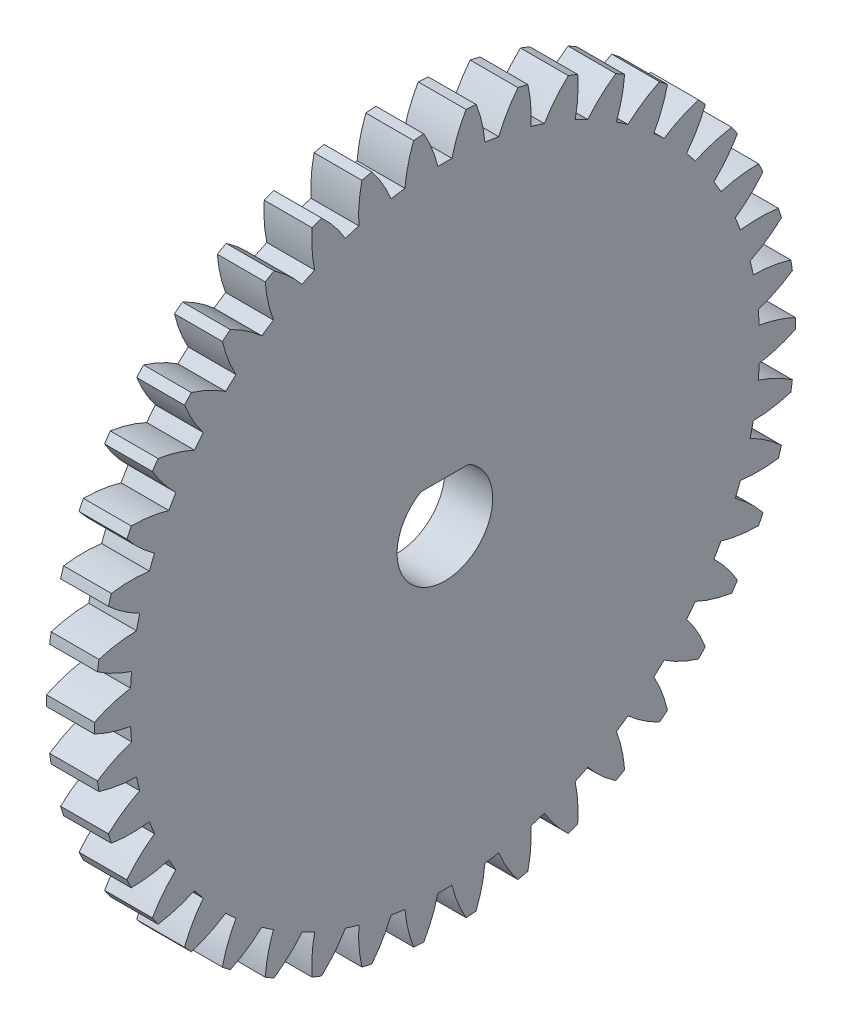
SolidWorks part; units mm, degrees
ref_plane "Plane1" through (0, 0, 0) normal (0, 0, 1) x (1, 0, 0)
ref_plane "Plane2" through (0, 0, 0) normal (0, 1, 0) x (1, 0, 0)
ref_plane "Plane3" through (0, 0, 0) normal (1, 0, 0) x (0, 0, -1)
other "Configuration Table"
sketch "HoldingSke" plane through (0, 0, 0) normal (0, 1, 0) x (1, 0, 0)
  line L0 (0, 0) -> (0.3716, -0.3346)
  line L1 (-15, 0) -> (100, 0) construction
  line L2 (0, 0) -> (-2.1039, 2.3779)
  line L3 (0, 0) -> (-11.863, 4.5341)
  line L4 (0, 0) -> (6.4178, 5.7786)
  line L5 (0, 0) -> (-46.8476, -17.4728)
  line L6 (0, 0) -> (-4.9738, -3.3558)
  line L7 (-2.1039, 2.3779) -> (8.6586, 51.2059)
  line L8 (-76.2, 54.61) -> (-73.9, 54.61)
  line L9 (-71.009, 38.7566) -> (-53.1078, 45.2721)
  line L10 (-76.2, 71.12) -> (104.1128, 71.12)
  line L11 (0, 0) -> (-6, 0)
  line L12 (-76.2, 101.6) -> (-76.133, 101.6)
  line L13 (24.9733, 27.94) -> (52.9518, 28.4284)
  line L14 (24.9733, 27.94) -> (24.9743, 27.94)
  line L15 (24.9733, 27.94) -> (100.4006, 29.5858)
  line L16 (-63.627, -2) -> (-12.827, -2)
  circle A0 centre (0, 0) radius 6
  circle A1 centre (0, 0) radius 37.5
  circle A2 centre (0, 0) radius 37.5
  circle A3 centre (0, 0) radius 6
  dimension "MHD" = 75
  dimension "Hub_dia" = 75
  dimension "Bore" = 12
  dimension "MBD" = 12
  dimension "Num_teeth" = 42
  dimension "Pitch" = 0.5
  dimension "Overall_len" = 50
  dimension "Show_teeth" = 42
  dimension "Thickness" = 6
  dimension "OAL" = 50.0001
  dimension "T_dim" = 2.3
  dimension "Ap" = 20
  dimension "H" = 19.05
  dimension "Pitch_radius" = 180.3128
  dimension "Width" = 6
  dimension "Backlash" = 0.067
  dimension "Addendum_fac" = 1
  dimension "Dedendum_fac" = 1.25
  dimension "Clearance_fac" = 0.25
  dimension "Dedendum_add" = 0.001
  dimension "Module" = 2
sketch "BasProSke" plane through (0, 0, 0) normal (0, 1, 0) x (1, 0, 0)
  line L0 (-10, 0) -> (60, 0) construction
  line L1 (0, 0) -> (0, 44)
  line L2 (0, 0) -> (6, 0)
  line L3 (6, 0) -> (6, 44)
  line L4 (6, 44) -> (0, 44)
  dimension "Thickness" = 6
  dimension "Diameter" = 88
revolve "Base-Revolve" add sketch "BasProSke" angle 360 about L0
sketch "TooCutSke" plane through (0, 0, 0) normal (1, 0, 0) x (0, 0, -1)
  line L1 (0, 0) -> (0, 107) construction
  line L2 (0, 0) -> (-1.6877, 41.9661) construction
  line L3 (0, 0) -> (-6.2736, 83.715) construction
  line L4 (-1.6877, 41.9661) -> (-3.1368, 41.8575) construction
  arc A0 (0.8776, 39.4892) -> (-0.8776, 39.4892) centre (0, 0) ccw
  arc A1 (2.6666, 43.9446) -> (-2.6666, 43.9446) centre (0, 0) ccw
  circle A2 centre (0, 0) radius 42 construction
  circle A3 centre (0, 0) radius 39.4671 construction
  arc A4 (-0.8776, 39.4892) -> (-2.6666, 43.9446) centre (-17.2022, 35.5209) ccw
  arc A5 (2.6666, 43.9446) -> (0.8776, 39.4892) centre (17.2022, 35.5209) ccw
  dimension "Root_dia" = 78.998
  dimension "Overcut_dia" = 88.0508
  dimension "Pitch_dia" = 84
  dimension "Base_dia" = 78.9342
  dimension "Flank_rad" = 16.8
  dimension "Half_ang" = 4.286
  dimension "Half_CT" = 1.4532
extrude "ToothCut" cut sketch "TooCutSke" along normal through all
fillet "Breaks" [suppressed] radius 0.04
fillet "RootFillets" [suppressed] radius 0.501
pattern_circular "TeethCuts" count 42 every 8.571 about axis through (-10, 0, 0) along (1, 0, 0) of "ToothCut", "RootFillets", "Breaks"
sketch "HubNeaOneSke" plane through (0, 0, 0) normal (-1, 0, 0) x (0, 0, 1)
  circle A0 centre (0, 0) radius 37.5
  dimension "Diameter" = 75
extrude "HubNearOne" [suppressed] add sketch "HubNeaOneSke" along normal blind 44.0001
sketch "HubNeaBotSke" plane through (0, 0, 0) normal (-1, 0, 0) x (0, 0, 1)
  circle A0 centre (0, 0) radius 37.5
  dimension "Diameter" = 75
extrude "HubNearBoth" [suppressed] add sketch "HubNeaBotSke" along normal blind 22
ref_plane "FarPln" through (6, 0, 0) normal (1, 0, 0) x (0, 0, -1)
sketch "HubFarSke" plane through (6, 0, 0) normal (1, 0, 0) x (0, 0, -1)
  circle A0 centre (0, 0) radius 37.5
  dimension "Diameter" = 75
extrude "HubFar" [suppressed] add sketch "HubFarSke" along normal blind 22
sketch "BorSke" plane through (0, 0, 0) normal (1, 0, 0) x (0, 0, -1)
  circle A0 centre (0, 0) radius 6
  dimension "Diameter" = 12
extrude "Bore" cut sketch "BorSke" along normal mid plane 100.0001
sketch "KeySke" plane through (0, 0, 0) normal (1, 0, 0) x (0, 0, -1)
  line L0 (-2.5, 0) -> (-2.5, 8.3)
  line L1 (-2.5, 8.3) -> (2.5, 8.3)
  line L2 (2.5, 8.3) -> (2.5, 0)
  line L3 (0, 0) -> (0, 34) construction
  line L4 (-2.5, 0) -> (2.5, 0)
  dimension "Offset" = 8.3
  dimension "Width" = 5
extrude "Keyway" [suppressed] cut sketch "KeySke" along normal mid plane 100.0001
pattern_circular "Keyway2" [suppressed] count 2 every 90 about axis through (-10, 0, 0) along (1, 0, 0)
sketch "Sketch1" plane through (6, 0, 0) normal (1, 0, 0) x (0, 0, -1)
  line L0 (-3, 5.1962) -> (3, 5.1962)
  circle A0 centre (0, 0) radius 6 construction
  circle A2 centre (0, 0) radius 6
  arc A3 (3, 5.1962) -> (-3, 5.1962) centre (0, 0) ccw
  dimension "D1" = 6
  dimension "D2" = 0
extrude "Boss-Extrude1" add sketch "Sketch1" against normal blind 6
equation "' \"Module@HoldingSke\" = 6.35"
equation "' \"Num_teeth@HoldingSke\" = 12"
equation "' \"Ap@HoldingSke\" =  20"
equation "' \"Ap@HoldingSke\" = 20"
equation "' \"Width@HoldingSke\" = 0.5 * 25.4"
equation "' \"Hub_dia@HoldingSke\"= 1 * 25.4"
equation "' \"Hub_dia@HoldingSke\" = 1 * 25.4"
equation "' \"Overall_len@HoldingSke\" = 1.0 * 25.4"
equation "' \"Bore@HoldingSke\" = 0.75 * 25.4"
equation "' \"T_dim@HoldingSke\" = 0.1 * 25.4"
equation "' \"Width@KeySke\" = 0.25 * 25.4"
equation "' \"Show_teeth@HoldingSke\" = 13"
equation "' \"Backlash@HoldingSke\" = 0.009 * 25.4"
equation "' \"Addendum_fac@HoldingSke\" = 1.0"
equation "' \"Dedendum_fac@HoldingSke\" = 1.25"
equation "' \"Dedendum_add@HoldingSke\" = 0.00005 * 25.4"
equation "' \"Clearance_fac@HoldingSke\" = 0.25"
equation "\"Pitch@HoldingSke\" = 1 / \"Module@HoldingSke\""
equation "\"Overcut_dia@TooCutSke\" = (\"Num_teeth@HoldingSke\" + 2 * \"Addendum_fac@HoldingSke\") / \"Pitch@HoldingSke\" + 0.002 * 25.4"
equation "\"Pitch_dia@TooCutSke\" = \"Num_teeth@HoldingSke\" / \"Pitch@HoldingSke\""
equation "\"Base_dia@TooCutSke\" = \"Num_teeth@HoldingSke\" / \"Pitch@HoldingSke\" * cos((\"Ap@HoldingSke\"  * 3.14159265 / 180))"
equation "\"Root_dia@TooCutSke\" = (\"Num_teeth@HoldingSke\" + 2) / \"Pitch@HoldingSke\" - 2 * (\"Addendum_fac@HoldingSke\" + \"Dedendum_fac@HoldingSke\") / \"Pitch@HoldingSke\" - \"Dedendum_add@HoldingSke\" * 2"
equation "\"Half_ang@TooCutSke\" = 180 / \"Num_teeth@HoldingSke\""
equation "\"Half_CT@TooCutSke\" = \"Num_teeth@HoldingSke\" / \"Pitch@HoldingSke\" * sin((3.14159265 / 2 / \"Num_teeth@HoldingSke\")) / 2 - 7 * \"Backlash@HoldingSke\" / 4"
equation "\"Flank_rad@TooCutSke\" = \"Num_teeth@HoldingSke\" / \"Pitch@HoldingSke\" / 5"
equation "\"Radius@RootFillets\" = \"Clearance_fac@HoldingSke\" / \"Pitch@HoldingSke\" + \"Dedendum_add@HoldingSke\""
equation "\"Break_rad@Breaks\" = 0.02 / \"Pitch@HoldingSke\""
equation "\"Thickness@HoldingSke\" = \"Width@HoldingSke\""
equation "\"OAL@HoldingSke\" = \"Thickness@HoldingSke\""
equation "\"MHD@HoldingSke\" = (\"Num_teeth@HoldingSke\" + 2) / \"Pitch@HoldingSke\" - 2 * (\"Addendum_fac@HoldingSke\" + \"Dedendum_fac@HoldingSke\")  / \"Pitch@HoldingSke\" - \"Dedendum_add@HoldingSke\" * 2"
equation "\"MBD@HoldingSke\" = (\"Num_teeth@HoldingSke\" + 2) / \"Pitch@HoldingSke\" - 2 * (\"Addendum_fac@HoldingSke\" + \"Dedendum_fac@HoldingSke\")  / \"Pitch@HoldingSke\" - \"Dedendum_add@HoldingSke\" * 2 - 0.002 * 25.4"
equation "\"MHD@HoldingSke\" = ((sgn( \"MHD@HoldingSke\" - \"Hub_dia@HoldingSke\" )-1)*( \"MHD@HoldingSke\" - \"Hub_dia@HoldingSke\" ))/-2+ \"Hub_dia@HoldingSke\""
equation "\"MBD@HoldingSke\" = ((sgn( \"MBD@HoldingSke\" - \"Bore@HoldingSke\" )-1)*( \"MBD@HoldingSke\" - \"Bore@HoldingSke\" ))/-2+ \"Bore@HoldingSke\""
equation "\"OAL@HoldingSke\" = ((sgn( \"OAL@HoldingSke\" - \"Overall_len@HoldingSke\" )+1)*( \"OAL@HoldingSke\" - \"Overall_len@HoldingSke\" ))/2 + \"Overall_len@HoldingSke\" + 0.000002 * 25.4"
equation "\"Num_teeth@TeethCuts\" = int( \"Show_teeth@HoldingSke\" ) + 1"
equation "\"Num_teeth@TeethCuts\" = ((sgn( \"Num_teeth@TeethCuts\" - \"Num_teeth@HoldingSke\" )-1)*( \"Num_teeth@TeethCuts\" - \"Num_teeth@HoldingSke\" ))/-2+ \"Num_teeth@HoldingSke\""
equation "\"Num_teeth@TeethCuts\" = ((sgn( \"Num_teeth@TeethCuts\" - 2.0)+1)*( \"Num_teeth@TeethCuts\" - 2.0))/2 +2.0"
equation "\"Angle@TeethCuts\" = 360.0 / \"Num_teeth@HoldingSke\""
equation "\"Diameter@BasProSke\" = (\"Num_teeth@HoldingSke\" + 2 * \"Addendum_fac@HoldingSke\") / \"Pitch@HoldingSke\""
equation "\"Thickness@BasProSke\"  = \"Thickness@HoldingSke\""
equation "' \"Fillet_rad@BasProSke\" =  \"Thickness@HoldingSke\" * 0.05"
equation "' \"Fillet_rad@BasProSke\" = \"Thickness@HoldingSke\" * 0.05"
equation "\"MHD@HoldingSke\" = ((sgn( \"MHD@HoldingSke\" - \"Root_dia@TooCutSke\" )-1)*( \"MHD@HoldingSke\" - \"Root_dia@TooCutSke\" ))/-2+ \"Root_dia@TooCutSke\""
equation "\"Diameter@HubNeaOneSke\" = \"MHD@HoldingSke\""
equation "\"Length@HubNearOne\" = \"OAL@HoldingSke\" - \"Thickness@BasProSke\""
equation "\"Diameter@HubNeaBotSke\" = \"MHD@HoldingSke\""
equation "\"Length@HubNearBoth\" = ( \"OAL@HoldingSke\" - \"Thickness@BasProSke\" ) / 2.0"
equation "\"Thickness@FarPln\" = \"Thickness@BasProSke\""
equation "\"Diameter@HubFarSke\" = \"MHD@HoldingSke\""
equation "\"Length@HubFar\" = ( \"OAL@HoldingSke\" - \"Thickness@BasProSke\" ) / 2.0"
equation "\"Diameter@BorSke\" = \"MBD@HoldingSke\""
equation "\"D1@Bore\" = \"OAL@HoldingSke\" * 2.0"
equation "\"D1@Keyway\" = \"OAL@HoldingSke\" * 2.0"
equation "\"Offset@KeySke\" = \"T_dim@HoldingSke\" + \"MBD@HoldingSke\" / 2.0"
